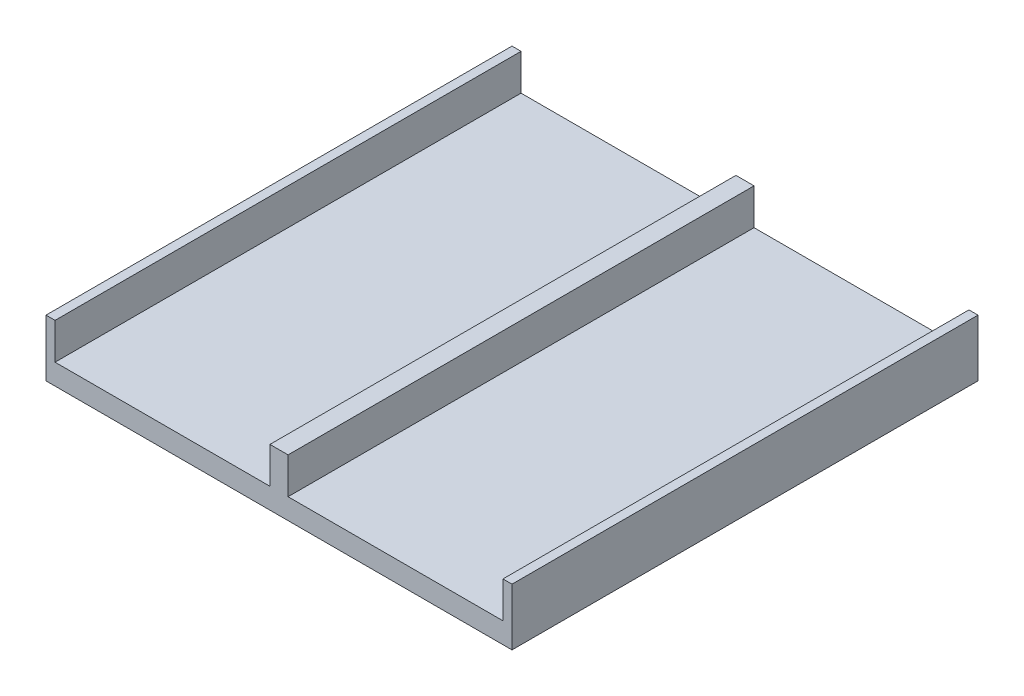
SolidWorks part; units mm, degrees
ref_plane "Front Plane" through (0, 0, 0) normal (0, 0, 1) x (1, 0, 0)
ref_plane "Top Plane" through (0, 0, 0) normal (0, 1, 0) x (1, 0, 0)
ref_plane "Right Plane" through (0, 0, 0) normal (1, 0, 0) x (0, 0, -1)
sketch "Sketch1" plane through (0, 0, 0) normal (0, 1, 0) x (1, 0, 0)
  line L1 (-45, 45) -> (45, 45)
  line L2 (-45, 45) -> (-45, -45)
  line L3 (-45, -45) -> (45, -45)
  line L4 (45, 45) -> (45, -45)
  line L5 (-45, 45) -> (45, -45) construction
  line L6 (-45, -45) -> (45, 45) construction
  point P0 (0, 0)
  dimension "D1" = 90
  dimension "D2" = 90
extrude "Boss-Extrude1" add sketch "Sketch1" along normal blind 11
sketch "Sketch2" plane through (0, 11, 0) normal (0, 1, 0) x (1, 0, 0)
  line L0 (0, 45) -> (0, -45) construction
  line L1 (45, 45) -> (-45, 45) construction
  line L2 (-45, -45) -> (45, -45) construction
  line L3 (-1.75, 45) -> (-1.75, -45) construction
  line L4 (1.75, 45) -> (1.75, -45) construction
  line L5 (-43.25, 45) -> (-43.25, -45) construction
  line L6 (-45, 45) -> (-45, -45) construction
  line L7 (43.25, 45) -> (43.25, -45) construction
  line L8 (-43.25, 45) -> (-1.75, 45)
  line L9 (-43.25, 45) -> (-43.25, -45)
  line L10 (-43.25, -45) -> (-1.75, -45)
  line L11 (-1.75, 45) -> (-1.75, -45)
  line L12 (45, -45) -> (45, 45) construction
  line L14 (1.75, 45) -> (43.25, 45)
  line L15 (1.75, 45) -> (1.75, -45)
  line L16 (1.75, -45) -> (43.25, -45)
  line L17 (43.25, 45) -> (43.25, -45)
  dimension "D1" = 1.75
  dimension "D2" = 1.75
  dimension "D3" = 1.75
  dimension "D4" = 1.75
extrude "Cut-Extrude2" cut sketch "Sketch2" against normal blind 7
